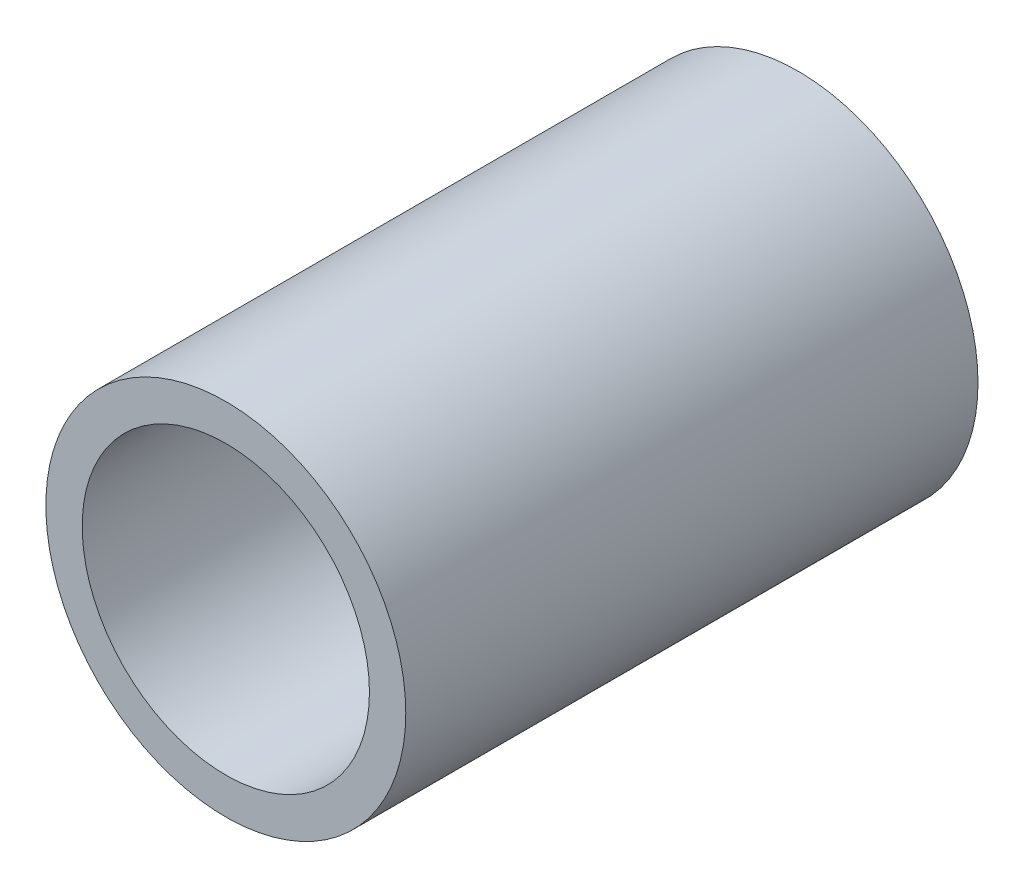
SolidWorks part; units mm, degrees
ref_plane "Front Plane" through (0, 0, 0) normal (0, 0, 1) x (1, 0, 0)
ref_plane "Top Plane" through (0, 0, 0) normal (0, 1, 0) x (1, 0, 0)
ref_plane "Right Plane" through (0, 0, 0) normal (1, 0, 0) x (0, 0, -1)
sketch "Sketch1" plane through (0, 0, 0) normal (0, 0, 1) x (1, 0, 0)
  circle A0 centre (0, 0) radius 3.9942
  circle A1 centre (0, 0) radius 3.1877
  dimension "OD" = 7.9883
  dimension "ID" = 6.3754
sketch "Sketch2" plane through (0, 0, 0) normal (1, 0, 0) x (0, 0, -1)
  line L2 (6.35, 0) -> (-6.35, 0) construction
  line L4 (-6.35, -3.9942) -> (-6.35, 3.9941) construction
  line L5 (-6.35, -3.1877) -> (6.35, -3.1877)
  line L6 (6.35, 3.1877) -> (-6.35, 3.1877)
  line L7 (6.35, -3.9941) -> (6.35, 3.9941) construction
  line L8 (-6.35, 3.9941) -> (6.35, 3.9941) construction
  line L9 (-6.35, -3.9942) -> (6.35, -3.9941) construction
  line L10 (0, 3.9942) -> (0, -3.9942) construction
  line L11 (0, 3.1877) -> (0, -3.1877) construction
  point P4 (0, -3.1877)
  point P7 (0, 3.1877)
  point P8 (0, 0)
  point P12 (-6.35, 0)
  point P15 (6.35, 0)
  point P16 (0, -3.9942)
  point P17 (0, 3.9942)
  dimension "Length" = 12.7
sketch "Sketch5" plane through (0, 0, 0) normal (0, 0, 1) x (1, 0, 0)
  circle A1 centre (0, 0) radius 3.1877
  circle A2 centre (0, 0) radius 3.1877
  circle A3 centre (0, 0) radius 3.9942
  circle A4 centre (0, 0) radius 3.9942
  dimension "D1" = 0
  dimension "D2" = 0
extrude "Boss-Extrude1" add sketch "Sketch5" along normal up to vertex (6.35 mm away) and the other way up to vertex (6.35 mm away) up to point (0, 0, 6.35) other way up to point (0, 0, -6.35)
sketch "Sketch4" plane through (0, 0, 6.35) normal (0, 0, 1) x (1, 0, 0)
  line L0 (0, 0) -> (-2.254, 2.254)
  line L2 (0, -3.9942) -> (0, 3.9941) construction
  circle A1 centre (0, 0) radius 3.1877 construction
  dimension "D1" = 45
equation "\"D1\"= \"Length@Sketch2\""
